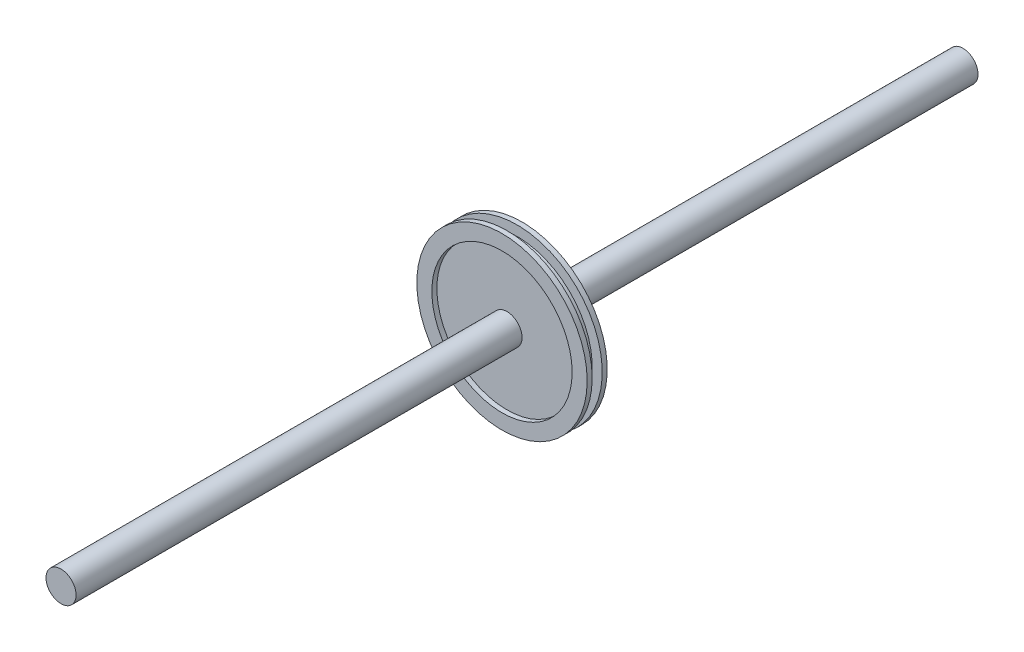
SolidWorks part; units mm, degrees
ref_plane "Front Plane" through (0, 0, 0) normal (0, 0, 1) x (1, 0, 0)
ref_plane "Top Plane" through (0, 0, 0) normal (0, 1, 0) x (1, 0, 0)
ref_plane "Right Plane" through (0, 0, 0) normal (1, 0, 0) x (0, 0, -1)
sketch "Sketch1" plane through (0, 0, 0) normal (0, 0, 1) x (1, 0, 0)
  circle A0 centre (0, 0) radius 7.5
  dimension "D1" = 15
extrude "Boss-Extrude1" add sketch "Sketch1" along normal mid plane 1
sketch "Sketch3" plane through (0, 0, 0.5) normal (0, 0, 1) x (1, 0, 0)
  circle A0 centre (0, 0) radius 8.5
  circle A3 centre (0, 0) radius 7
  dimension "D1" = 14
  dimension "D2" = 17
extrude "Boss-Extrude2" add sketch "Sketch3" along normal blind 0.5
sketch "Sketch4" plane through (0, 0, -0.5) normal (0, 0, -1) x (-1, 0, 0)
  circle A0 centre (0, 0) radius 7
  circle A1 centre (0, 0) radius 8.5
  dimension "D1" = 17
  dimension "D2" = 14
extrude "Boss-Extrude3" add sketch "Sketch4" along normal blind 0.5
sketch "Sketch6" plane through (0, 0, 0) normal (0, 0, 1) x (1, 0, 0)
  circle A0 centre (0, 0) radius 1.5
extrude "Boss-Extrude4" add sketch "Sketch6" along normal mid plane 90
